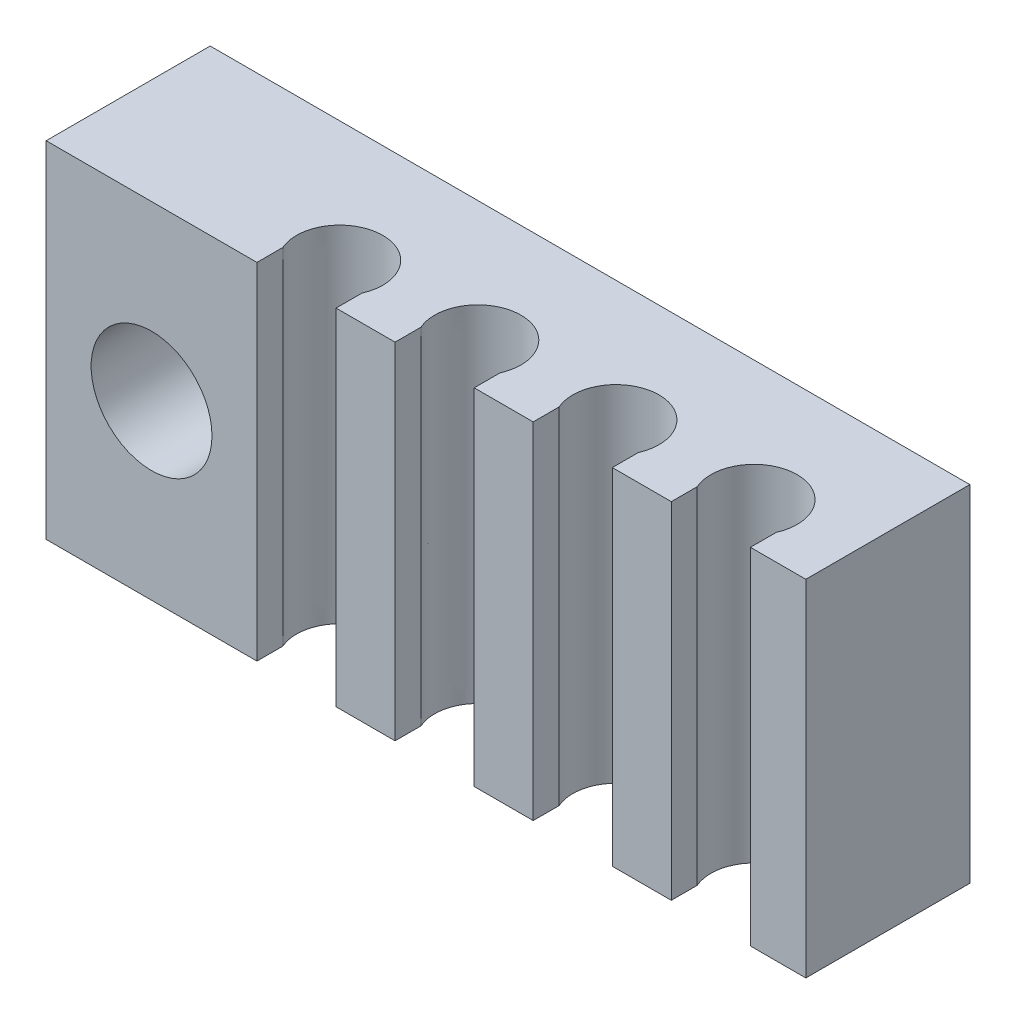
SolidWorks part; units mm, degrees
ref_plane "Front Plane" through (0, 0, 0) normal (0, 0, 1) x (1, 0, 0)
ref_plane "Top Plane" through (0, 0, 0) normal (0, 1, 0) x (1, 0, 0)
ref_plane "Right Plane" through (0, 0, 0) normal (1, 0, 0) x (0, 0, -1)
sketch "Sketch1" plane through (0, 0, 0) normal (0, 1, 0) x (1, 0, 0)
  line L0 (2.25, 0.5) -> (2.25, 0) construction
  line L1 (0, 0) -> (1.1044, 0)
  line L2 (0, 0) -> (0, 4)
  line L3 (0, 4) -> (17, 4)
  line L4 (17, 0) -> (17, 4)
  line L5 (1, 0.5) -> (0, 0.5) construction
  line L6 (3.5, 0.5) -> (5, 0.5) construction
  line L7 (-5, 0) -> (-5, -0.75)
  line L8 (0, 4) -> (-5, 4)
  line L9 (0, 4) -> (0, 0)
  line L10 (0, 0) -> (-5, 0)
  line L11 (-5, 4) -> (-5, 0)
  line L12 (-5, -0.75) -> (17, -0.75)
  line L13 (17, -0.75) -> (17, 0)
  line L14 (3.3956, 0) -> (5.1044, 0)
  line L15 (7.3956, 0) -> (17, 0)
  line L16 (1.1044, 0) -> (1.1044, -0.75)
  line L17 (3.3956, 0) -> (3.3956, -0.75)
  line L18 (5.1044, 0) -> (5.1044, -0.75)
  line L19 (7.3956, 0) -> (7.3956, -0.75)
  line L20 (7.3956, 0) -> (9.1044, 0)
  line L21 (9.1044, 0) -> (9.1044, -0.75)
  line L22 (11.3956, 0) -> (11.3956, -0.75)
  line L23 (11.3956, 0) -> (13.1044, 0)
  line L24 (13.1044, 0) -> (13.1044, -0.75)
  line L25 (15.3956, 0) -> (15.3956, -0.75)
  line L26 (7.5, 0.5) -> (9, 0.5) construction
  arc A0 (3.3956, 0) -> (1.1044, 0) centre (2.25, 0.5) ccw
  arc A1 (7.3956, 0) -> (5.1044, 0) centre (6.25, 0.5) ccw
  arc A2 (11.3956, 0) -> (9.1044, 0) centre (10.25, 0.5) ccw
  arc A3 (15.3956, 0) -> (13.1044, 0) centre (14.25, 0.5) ccw
  dimension "D2" = 2.5
  dimension "D7" = 1.5
  dimension "D10" = 1.5
  dimension "D1" = 4
  dimension "D3" = 0.5
  dimension "D4" = 1
  dimension "D5" = 17
  dimension "D8" = 5
  dimension "D9" = 3
  dimension "D6" = 2
extrude "Boss-Extrude1" add sketch "Sketch1" along normal blind 10 contours L8 L11 L10 L2 | A1 L1 L4 L3 L2 A0 | L16 L1 L10 L7 L12 | L18 L14 L17 L12 | L15 L19 L12 L13 | L24 L15 L22 L12 | L15 L25 L12 L13
sketch "Sketch4" plane through (0, 0, 0.75) normal (0, 0, 1) x (1, 0, 0)
  line L0 (-5, 10) -> (1.1044, 0) construction
  circle A0 centre (-1.9478, 5) radius 1.75
  dimension "D1" = 3.5
extrude "Cut-Extrude2" cut sketch "Sketch4" against normal through all
